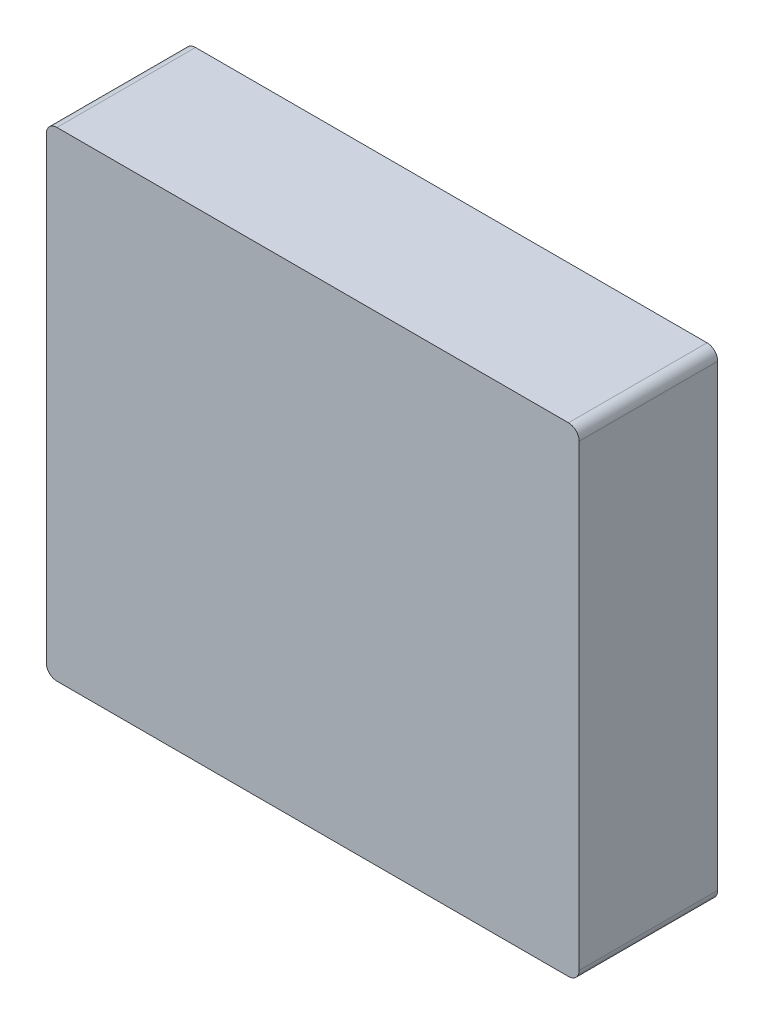
SolidWorks part; units mm, degrees
ref_plane "Спереди" through (0, 0, 0) normal (0, 0, 1) x (1, 0, 0)
ref_plane "Сверху" through (0, 0, 0) normal (0, 1, 0) x (1, 0, 0)
ref_plane "Справа" through (0, 0, 0) normal (1, 0, 0) x (0, 0, -1)
sketch "Эскиз1" plane through (0, 0, 0) normal (0, 0, 1) x (1, 0, 0)
  line L4 (-48, -45) -> (48, -45)
  line L5 (50, -43) -> (50, 43)
  line L6 (48, 45) -> (-48, 45)
  line L7 (-50, 43) -> (-50, -43)
  arc A4 (-50, -43) -> (-48, -45) centre (-48, -43) ccw
  arc A5 (48, -45) -> (50, -43) centre (48, -43) ccw
  arc A6 (50, 43) -> (48, 45) centre (48, 43) ccw
  arc A7 (-48, 45) -> (-50, 43) centre (-48, 43) ccw
extrude "Бобышка-Вытянуть1" add sketch "Эскиз1" along normal blind 26
sketch "Эскиз2" plane through (0, 0, 0) normal (0, 0, -1) x (-1, 0, 0)
  line L1 (-47.5, -42.5) -> (-47.5, 42.5)
  line L3 (-47.5, 42.5) -> (47.5, 42.5)
  line L5 (47.5, 42.5) -> (47.5, -42.5)
  line L7 (47.5, -42.5) -> (-47.5, -42.5)
extrude "Вырез-Вытянуть1" cut sketch "Эскиз2" against normal blind 23
sketch "Эскиз3" plane through (0, 0, 0) normal (0, 0, -1) x (-1, 0, 0)
  line L0 (47.5, 42.5) -> (-47.5, 42.5) construction
  line L8 (-48, -43) -> (48, -43)
  line L9 (48, -43) -> (48, 43)
  line L10 (-48, 43) -> (-48, -43)
  line L11 (48, 43) -> (-48, 43)
  line L12 (-48, -43) -> (48, -43)
  line L13 (48, -43) -> (48, 43)
  line L14 (-48, 43) -> (-48, -43)
  line L15 (48, 43) -> (-48, 43)
  dimension "D1" = 0.5
extrude "Вырез-Вытянуть2" cut sketch "Эскиз3" against normal blind 23
fillet "Скругление1" radius 1 4 edges at (0, 43, 23) (-48, 0, 23) (0, -43, 23) (48, 0, 23)
fillet "Скругление2" radius 0.5 4 edges at (0, 43, 0) (48, 0, 0) (0, -43, 0) (-48, 0, 0)
